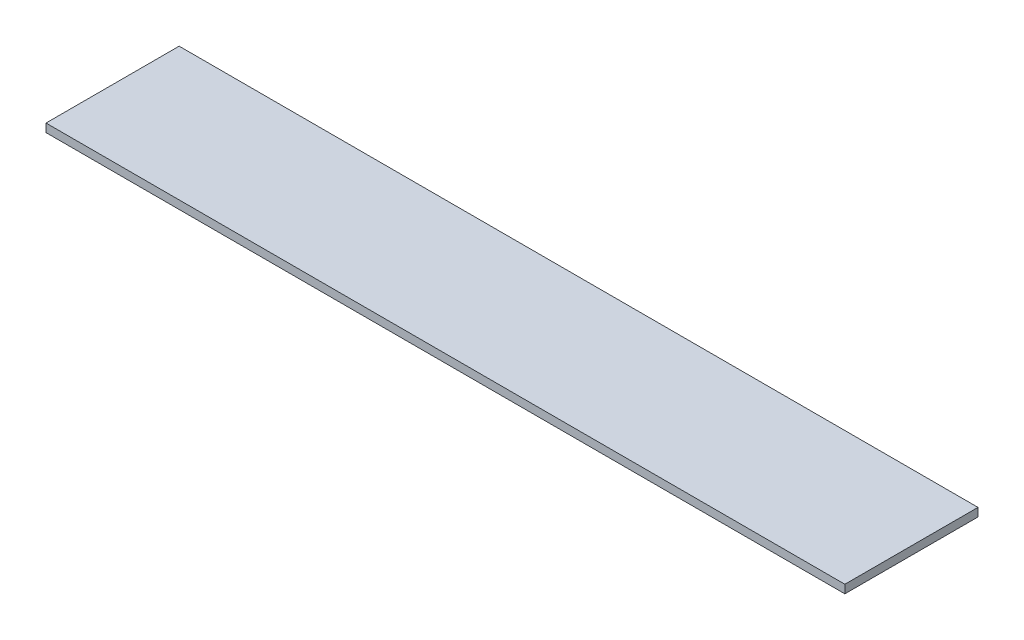
SolidWorks part; units mm, degrees
ref_plane "Front Plane" through (0, 0, 0) normal (0, 0, 1) x (1, 0, 0)
ref_plane "Top Plane" through (0, 0, 0) normal (0, 1, 0) x (1, 0, 0)
ref_plane "Right Plane" through (0, 0, 0) normal (1, 0, 0) x (0, 0, -1)
sketch "Sketch1" plane through (0, 0, 0) normal (0, 0, 1) x (1, 0, 0)
  line L1 (-28.3111, 16.1056) -> (67.6889, 16.1056)
  line L2 (-28.3111, 16.1056) -> (-28.3111, 0.1056)
  line L3 (-28.3111, 0.1056) -> (67.6889, 0.1056)
  line L4 (67.6889, 16.1056) -> (67.6889, 0.1056)
  line L5 (19.6889, 0.1056) -> (19.6889, 16.1056) construction
  line L6 (-28.3111, 8.1056) -> (67.6889, 8.1056) construction
  point P104 (19.6889, 8.1056)
  dimension "D1" = 16
  dimension "D2" = 96
extrude "Boss-Extrude1" add sketch "Sketch1" along normal blind 1
move or copy body "Body-Move/Copy1" bodies to move or copy 102 copy no rotation origin (0, 8.1056, 0.25) rotation axis (1, 0, 0) rotation angle 90
